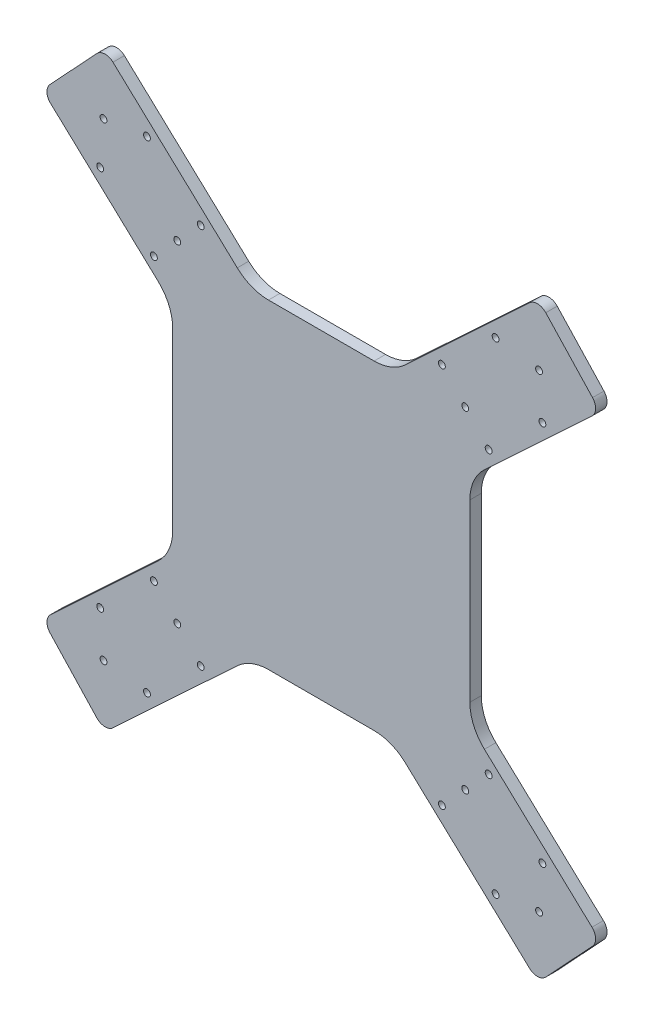
SolidWorks part; units mm, degrees
ref_plane "前视基准面" through (0, 0, 0) normal (0, 0, 1) x (1, 0, 0)
ref_plane "上视基准面" through (0, 0, 0) normal (0, 1, 0) x (1, 0, 0)
ref_plane "右视基准面" through (0, 0, 0) normal (1, 0, 0) x (0, 0, -1)
sketch "草图2" plane through (0, 0, 0) normal (0, 0, 1) x (1, 0, 0)
  line L0 (2886.4701, 1899.4965) -> (2857.2159, 1872.2166)
  line L1 (2857.2159, 1872.2166) -> (2870.8559, 1857.5895)
  line L2 (2870.8559, 1857.5895) -> (2900.1101, 1884.8695)
  line L3 (2886.4701, 1899.4965) -> (2900.1101, 1884.8695)
  line L4 (2769.0664, 1854.1359) -> (2815.2858, 1854.1359)
  line L5 (2857.1761, 1822.4634) -> (2857.1761, 1745.8085)
  line L6 (2815.2858, 1714.1359) -> (2769.0664, 1714.1359)
  line L7 (2727.1761, 1745.8085) -> (2727.1761, 1822.4634)
  line L8 (2697.8821, 1899.4965) -> (2727.1362, 1872.2166)
  line L9 (2727.1362, 1872.2166) -> (2713.4963, 1857.5895)
  line L10 (2713.4963, 1857.5895) -> (2684.2421, 1884.8695)
  line L11 (2697.8821, 1899.4965) -> (2684.2421, 1884.8695)
  line L12 (2886.4701, 1668.7753) -> (2857.2159, 1696.0552)
  line L13 (2857.2159, 1696.0552) -> (2870.8559, 1710.6823)
  line L14 (2870.8559, 1710.6823) -> (2900.1101, 1683.4024)
  line L15 (2886.4701, 1668.7753) -> (2900.1101, 1683.4024)
  line L16 (2697.8821, 1668.7753) -> (2727.1362, 1696.0552)
  line L17 (2727.1362, 1696.0552) -> (2713.4963, 1710.6823)
  line L18 (2713.4963, 1710.6823) -> (2684.2421, 1683.4024)
  line L19 (2697.8821, 1668.7753) -> (2684.2421, 1683.4024)
  line L20 (2720.8161, 1837.0904) -> (2673.7654, 1880.9659)
  line L21 (2755.4264, 1859.5088) -> (2701.0453, 1910.2201)
  line L22 (2693.9785, 1909.9733) -> (2673.5186, 1888.0327)
  line L23 (2863.5361, 1837.0904) -> (2910.5868, 1880.9659)
  line L24 (2828.9258, 1859.5088) -> (2883.3069, 1910.2201)
  line L25 (2890.3736, 1909.9733) -> (2910.8336, 1888.0327)
  line L26 (2720.8161, 1731.1814) -> (2673.7654, 1687.3059)
  line L27 (2755.4264, 1708.763) -> (2701.0453, 1658.0518)
  line L28 (2693.9785, 1658.2986) -> (2673.5186, 1680.2392)
  line L29 (2863.5361, 1731.1814) -> (2910.5868, 1687.3059)
  line L30 (2828.9258, 1708.763) -> (2883.3069, 1658.0518)
  line L31 (2890.3736, 1658.2986) -> (2910.8336, 1680.2392)
  circle A0 centre (2892.8055, 1898.5678) radius 1.5
  circle A1 centre (2899.6255, 1891.2542) radius 1.5
  circle A2 centre (2857.7005, 1865.8318) radius 1.5
  circle A3 centre (2864.5205, 1858.5183) radius 1.5
  arc A4 (2857.1761, 1745.8085) -> (2863.5361, 1731.1814) centre (2877.1761, 1745.8085) ccw
  arc A5 (2769.0664, 1714.1359) -> (2755.4264, 1708.763) centre (2769.0664, 1694.1359) ccw
  arc A6 (2727.1761, 1822.4634) -> (2720.8161, 1837.0904) centre (2707.1761, 1822.4634) ccw
  circle A7 centre (2691.5467, 1898.5678) radius 1.5
  circle A8 centre (2684.7267, 1891.2542) radius 1.5
  circle A9 centre (2726.6517, 1865.8318) radius 1.5
  circle A10 centre (2719.8317, 1858.5183) radius 1.5
  circle A11 centre (2892.8055, 1669.7041) radius 1.5
  circle A12 centre (2899.6255, 1677.0176) radius 1.5
  circle A13 centre (2857.7005, 1702.44) radius 1.5
  circle A14 centre (2864.5205, 1709.7535) radius 1.5
  circle A15 centre (2691.5467, 1669.7041) radius 1.5
  circle A16 centre (2684.7267, 1677.0176) radius 1.5
  circle A17 centre (2726.6517, 1702.44) radius 1.5
  circle A18 centre (2719.8317, 1709.7535) radius 1.5
  arc A19 (2755.4264, 1859.5088) -> (2769.0664, 1854.1359) centre (2769.0664, 1874.1359) ccw
  arc A20 (2701.0453, 1910.2201) -> (2693.9785, 1909.9733) centre (2697.6353, 1906.5633) ccw
  arc A21 (2673.5186, 1888.0327) -> (2673.7654, 1880.9659) centre (2677.1754, 1884.6227) ccw
  arc A22 (2863.5361, 1837.0904) -> (2857.1761, 1822.4634) centre (2877.1761, 1822.4634) ccw
  arc A23 (2910.5868, 1880.9659) -> (2910.8336, 1888.0327) centre (2907.1768, 1884.6227) ccw
  arc A24 (2815.2858, 1854.1359) -> (2828.9258, 1859.5088) centre (2815.2858, 1874.1359) ccw
  arc A25 (2890.3736, 1909.9733) -> (2883.3069, 1910.2201) centre (2886.7169, 1906.5633) ccw
  arc A26 (2720.8161, 1731.1814) -> (2727.1761, 1745.8085) centre (2707.1761, 1745.8085) ccw
  arc A27 (2693.9785, 1658.2986) -> (2701.0453, 1658.0518) centre (2697.6353, 1661.7085) ccw
  arc A28 (2673.7654, 1687.3059) -> (2673.5186, 1680.2392) centre (2677.1754, 1683.6492) ccw
  arc A29 (2828.9258, 1708.763) -> (2815.2858, 1714.1359) centre (2815.2858, 1694.1359) ccw
  arc A30 (2883.3069, 1658.0518) -> (2890.3736, 1658.2986) centre (2886.7169, 1661.7085) ccw
  arc A31 (2910.8336, 1680.2392) -> (2910.5868, 1687.3059) centre (2907.1768, 1683.6492) ccw
extrude "凸台-拉伸1" add sketch "草图2" along normal blind 5 contours A6 L20 A21 L22 A20 L21 A19 L4 A24 L24 A25 L25 A23 L23 A22 L5 A4 L29 A31 L31 A30 L30 A29 L6 A5 L27 A27 L28 A28 L26 A26 L7
sketch "草图3" plane through (0, 0, 0) normal (0, 0, -1) x (-1, 0, 0)
  line L8 (-2886.4701, 1899.4965) -> (-2857.2159, 1872.2166)
  line L9 (-2857.2159, 1872.2166) -> (-2870.8559, 1857.5895)
  line L10 (-2870.8559, 1857.5895) -> (-2900.1101, 1884.8695)
  line L11 (-2886.4701, 1899.4965) -> (-2900.1101, 1884.8695)
  circle A34 centre (-2715.9192, 1889.5133) radius 1.5
  circle A35 centre (-2695.4592, 1867.5727) radius 1.5
  circle A36 centre (-2695.4592, 1700.6991) radius 1.5
  circle A37 centre (-2715.9192, 1678.7585) radius 1.5
  circle A38 centre (-2868.433, 1678.7585) radius 1.5
  circle A39 centre (-2888.893, 1700.6991) radius 1.5
  circle A40 centre (-2888.893, 1867.5727) radius 1.5
  circle A41 centre (-2868.433, 1889.5133) radius 1.5
  point P0 (0, 0)
  point P104 (0, 0)
extrude "切除-拉伸1" cut sketch "草图3" against normal blind 10 contours A38 | A39 | A40 | A41 | A35 | A34 | A37 | A36
sketch "草图4" plane through (0, 0, 0) normal (0, 0, -1) x (-1, 0, 0)
  line L0 (-2890.3736, 1909.9733) -> (-2910.8336, 1888.0327) construction
  line L4 (-2693.9785, 1909.9733) -> (-2673.5186, 1888.0327) construction
  line L7 (-2693.9785, 1658.2986) -> (-2673.5186, 1680.2392) construction
  line L8 (-2890.3736, 1658.2986) -> (-2910.8336, 1680.2392) construction
  circle A0 centre (-2887.4392, 1886.727) radius 1.5
  circle A1 centre (-2696.9129, 1886.727) radius 1.5
  circle A2 centre (-2696.9129, 1681.5448) radius 1.5
  circle A3 centre (-2887.4392, 1681.5448) radius 1.5
  point P3 (-2900.6036, 1899.003)
  point P7 (0, 0)
  dimension "D1" = 18
  dimension "D2" = 18
  dimension "D3" = 18
  dimension "D4" = 18
extrude "切除-拉伸2" cut sketch "草图4" against normal blind 10
sketch "草图5" plane through (0, 0, 0) normal (0, 0, -1) x (-1, 0, 0)
  circle A0 centre (-2739.4203, 1700.6736) radius 1.5
  circle A1 centre (-2718.9603, 1722.6142) radius 1.5
  circle A2 centre (-2729.1903, 1711.6439) radius 1.5
  circle A3 centre (-2729.1903, 1856.6279) radius 1.5
  circle A4 centre (-2718.9603, 1845.6576) radius 1.5
  circle A5 centre (-2739.4203, 1867.5982) radius 1.5
  circle A6 centre (-2844.9319, 1867.5982) radius 1.5
  circle A7 centre (-2865.3919, 1845.6576) radius 1.5
  circle A8 centre (-2855.1619, 1856.6279) radius 1.5
  circle A9 centre (-2855.1619, 1711.6439) radius 1.5
  circle A10 centre (-2865.3919, 1722.6142) radius 1.5
  circle A11 centre (-2844.9319, 1700.6736) radius 1.5
extrude "切除-拉伸3" cut sketch "草图5" against normal blind 33
